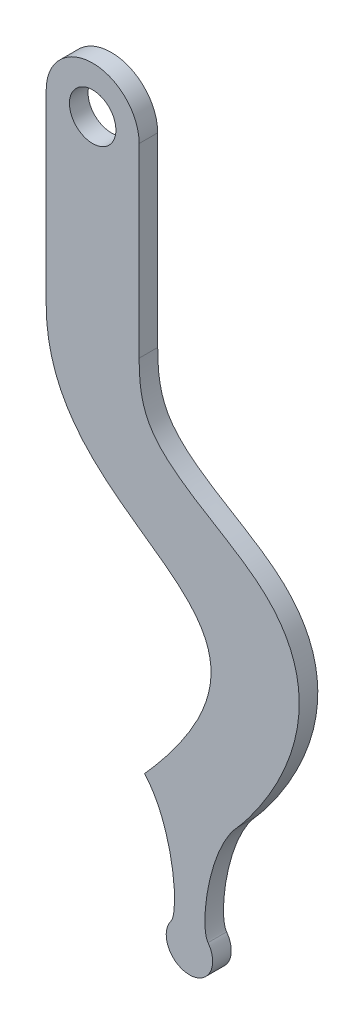
SolidWorks part; units mm, degrees
ref_plane "Alzado" through (0, 0, 0) normal (0, 0, 1) x (1, 0, 0)
ref_plane "Planta" through (0, 0, 0) normal (0, 1, 0) x (1, 0, 0)
ref_plane "Vista lateral" through (0, 0, 0) normal (1, 0, 0) x (0, 0, -1)
sketch "Croquis1" plane through (0, 0, 0) normal (0, 0, 1) x (1, 0, 0)
  line L0 (-1.953, -0.258) -> (-0.953, -0.258) construction
  line L1 (-0.953, -0.258) -> (-0.953, -2.258)
  line L2 (-1.953, -0.258) -> (-1.953, -2.258)
  line L3 (-1.453, -0.258) -> (-1.453, 0.6766) construction
  line L6 (-1.453, -0.258) -> (-1.453, -0.4127) construction
  line L7 (-0.8946, -6.1005) -> (0.1054, -6.1005) construction
  line L8 (-0.6117, -7.3339) -> (-0.2117, -7.3339) construction
  circle A0 centre (-1.453, -0.258) radius 0.25
  arc A1 (-0.953, -0.258) -> (-1.953, -0.258) centre (-1.453, -0.258) ccw
  arc A2 (-0.6117, -7.3339) -> (-0.2117, -7.3339) centre (-0.4117, -7.4839) ccw
  spline S0 degree 3 poles (-0.953, -2.258) (-0.953, -2.7776) (-0.7927, -3.0398) (1.6116, -4.3933) (0.1481, -6.0549) (0.1054, -6.1005) knots 0 0 0 0 0.302759 0.402759 1 1 1 1
  spline S1 degree 3 poles (-1.953, -2.258) (-1.953, -4.3245) (1.1931, -3.742) (-0.8946, -6.1005) knots 0 0 0 0 1 1 1 1
  spline S2 degree 3 poles (-0.2117, -7.3339) (-0.3029, -7.2123) (-0.2118, -6.4392) (0.1054, -6.1005) knots 0 0 0 0 1 1 1 1
  spline S3 degree 3 poles (-0.6117, -7.3339) (-0.5167, -7.2073) (-0.5849, -6.4343) (-0.8946, -6.1005) knots 0 0 0 0 1 1 1 1
  dimension "D1" = 2
extrude "Saliente-Extruir1" add sketch "Croquis1" along normal blind 0.2
